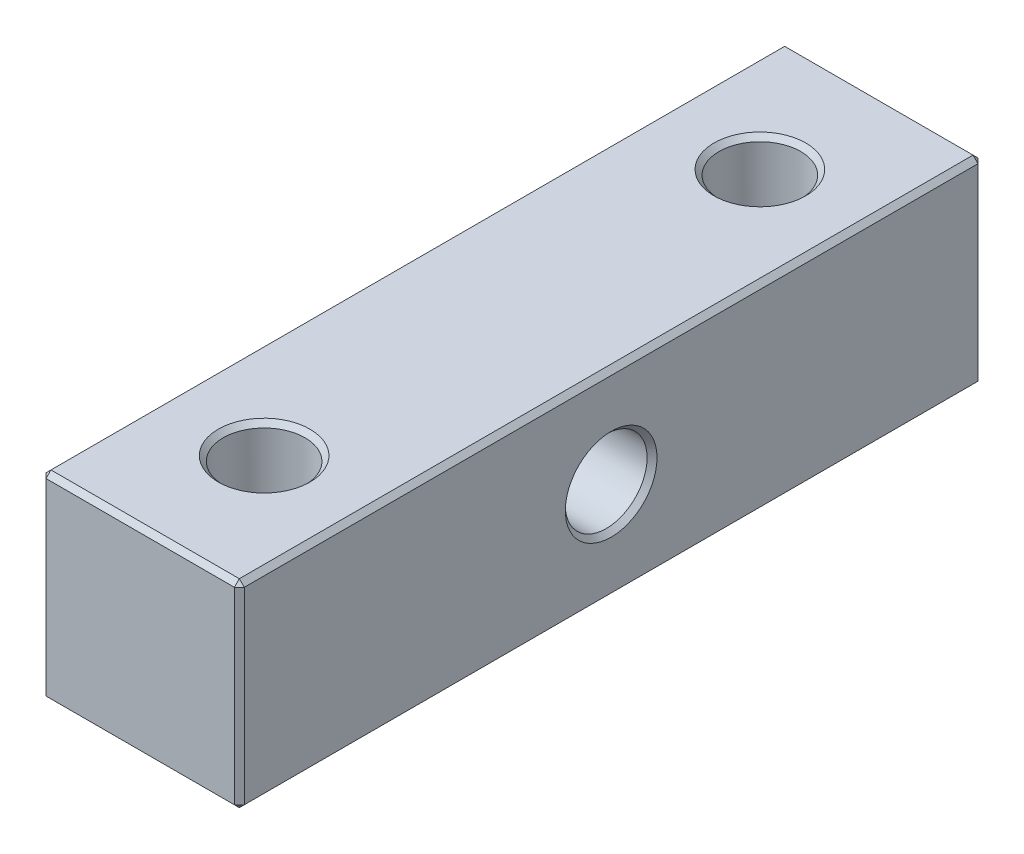
SolidWorks part; units mm, degrees
ref_plane "前视基准面" through (0, 0, 0) normal (0, 0, 1) x (1, 0, 0)
ref_plane "上视基准面" through (0, 0, 0) normal (0, 1, 0) x (1, 0, 0)
ref_plane "右视基准面" through (0, 0, 0) normal (1, 0, 0) x (0, 0, -1)
sketch "草图1" plane through (0, 0, 0) normal (0, 0, 1) x (1, 0, 0)
  line L1 (-4, 4) -> (4, 4)
  line L2 (-4, 4) -> (-4, -4)
  line L3 (-4, -4) -> (4, -4)
  line L4 (4, 4) -> (4, -4)
  line L5 (-4, 4) -> (4, -4) construction
  line L6 (-4, -4) -> (4, 4) construction
  point P0 (0, 0)
  dimension "D1" = 8
extrude "凸台-拉伸1" add sketch "草图1" along normal mid plane 30
hole_wizard "M4 螺纹孔1" positions "草图2" profile "草图3" tap size "M4" standard "GB" end condition through all
sketch "草图2" plane through (4, 0, 0) normal (1, 0, 0) x (0, 0, -1)
  line L0 (0, 0) -> (50000, 0) construction
  point P0 (0, 0)
  point P11 (0, 0)
  point P12 (0, 0)
sketch "草图3" plane through (4, 0, 0) normal (0, 1, 0) x (0, 0, -1)
  line L0 (0, 0) -> (0, 8)
  line L1 (0, 8) -> (1.65, 8)
  line L2 (1.65, 8) -> (1.65, 0)
  line L5 (1.65, 0) -> (0, 0)
  line L11 (0, -6.35) -> (0, 107.95) construction
  dimension "通孔螺纹孔钻头直径" = 3.3
  dimension "通孔螺纹孔钻头深度" = 8
cosmetic thread "孔螺蚊线3" parameters "D2"=4
hole_wizard "M4 螺纹孔2" positions "草图6" profile "草图7" tap size "M4" standard "GB" end condition through all
sketch "草图6" plane through (0, 4, 0) normal (0, 1, 0) x (1, 0, 0)
  line L0 (0, 0) -> (0, 50000) construction
  line L1 (0, 0) -> (50000, 0) construction
  point P0 (0, -10)
  point P2 (0, 10)
  dimension "D1" = 20
sketch "草图7" plane through (0, 4, 10) normal (1, 0, 0) x (0, 0, 1)
  line L0 (0, 0) -> (0, 8)
  line L1 (0, 8) -> (1.65, 8)
  line L2 (1.65, 8) -> (1.65, 0)
  line L5 (1.65, 0) -> (0, 0)
  line L11 (0, -6.35) -> (0, 107.95) construction
  dimension "通孔螺纹孔钻头直径" = 3.3
  dimension "通孔螺纹孔钻头深度" = 8
cosmetic thread "孔螺蚊线4"
cosmetic thread "孔螺蚊线5"
chamfer "倒角1" distance 0.2 angle 45 18 edges at (-4, 0, -1.65) (0, -4, 15) (0, -4, -15) (-4, -4, 0) (-4, 0, -15) (0, 4, 15) (-4, 4, 0) (0, 4, -15) (4, -4, 0) (4, 4, 0) (4, 0, -15) (4, 0, -1.65) (-4, 0, 15) (4, 0, 15) (0, -4, -8.35) (0, -4, 11.65) (0, 4, -8.35) (0, 4, 11.65)
